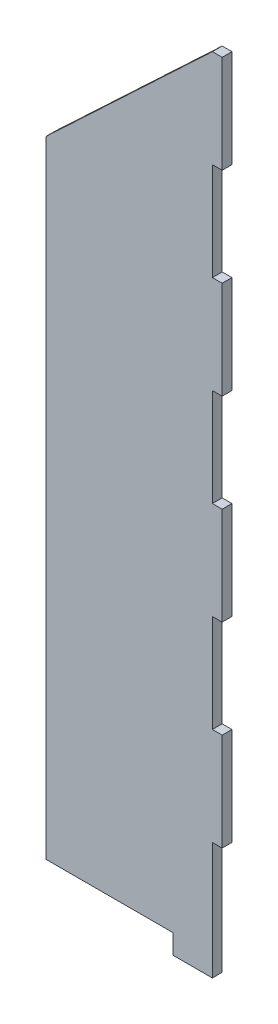
SolidWorks part; units mm, degrees
ref_plane "Front Plane" through (0, 0, 0) normal (0, 0, 1) x (1, 0, 0)
ref_plane "Top Plane" through (0, 0, 0) normal (0, 1, 0) x (1, 0, 0)
ref_plane "Right Plane" through (0, 0, 0) normal (1, 0, 0) x (0, 0, -1)
sketch "Sketch1" plane through (0, 0, 0) normal (0, 0, 1) x (1, 0, 0)
  line L0 (-26.9875, -101.6) -> (-26.9875, 101.6)
  line L1 (-26.9875, 101.6) -> (26.9875, 152.4)
  line L2 (26.9875, 152.4) -> (26.9875, -101.6)
  line L3 (26.9875, -101.6) -> (-26.9875, -101.6)
  line L4 (-26.9875, 0) -> (26.9875, 0) construction
  line L5 (26.9875, 120.65) -> (26.9875, 88.9)
  line L6 (26.9875, 152.4) -> (30.1625, 152.4)
  line L7 (26.9875, 152.4) -> (26.9875, 120.65)
  line L8 (26.9875, 120.65) -> (30.1625, 120.65)
  line L9 (30.1625, 152.4) -> (30.1625, 120.65)
  line L10 (26.9875, 120.65) -> (30.1625, 120.65)
  line L11 (30.1625, 120.65) -> (30.1625, 88.9)
  line L12 (26.9875, 88.9) -> (30.1625, 88.9)
  line L13 (26.9875, 88.9) -> (26.9875, 57.15)
  line L14 (26.9875, 88.9) -> (30.1625, 88.9)
  line L15 (30.1625, 88.9) -> (30.1625, 57.15)
  line L16 (26.9875, 57.15) -> (30.1625, 57.15)
  line L17 (26.9875, 57.15) -> (26.9875, 25.4)
  line L18 (26.9875, 57.15) -> (30.1625, 57.15)
  line L19 (30.1625, 57.15) -> (30.1625, 25.4)
  line L20 (26.9875, 25.4) -> (30.1625, 25.4)
  line L21 (26.9875, 25.4) -> (26.9875, -6.35)
  line L22 (26.9875, 25.4) -> (30.1625, 25.4)
  line L23 (30.1625, 25.4) -> (30.1625, -6.35)
  line L24 (26.9875, -6.35) -> (30.1625, -6.35)
  line L25 (26.9875, -6.35) -> (26.9875, -38.1)
  line L26 (26.9875, -6.35) -> (30.1625, -6.35)
  line L27 (30.1625, -6.35) -> (30.1625, -38.1)
  line L28 (26.9875, -38.1) -> (30.1625, -38.1)
  line L29 (26.9875, -38.1) -> (26.9875, -69.85)
  line L30 (26.9875, -38.1) -> (30.1625, -38.1)
  line L31 (30.1625, -38.1) -> (30.1625, -69.85)
  line L32 (26.9875, -69.85) -> (30.1625, -69.85)
  line L33 (26.9875, -69.85) -> (26.9875, -101.6)
  line L42 (26.9875, -69.85) -> (30.1625, -69.85)
  line L43 (30.1625, -69.85) -> (30.1625, -101.6)
  line L44 (26.9875, -101.6) -> (30.1625, -101.6)
  line L46 (14.2875, -101.6) -> (26.9875, -101.6)
  line L47 (14.2875, -101.6) -> (14.2875, -107.95)
  line L48 (14.2875, -107.95) -> (26.9875, -107.95)
  line L49 (26.9875, -101.6) -> (26.9875, -107.95)
  point P2 (0, 0)
  dimension "D1" = 53.975
  dimension "D2" = 254
  dimension "D3" = 203.2
  dimension "D4" = 3.175
  dimension "D6" = 31.75
  dimension "D7" = 12.7
  dimension "D8" = 6.35
  dimension "D5" = 8
extrude "Boss-Extrude1" add sketch "Sketch1" along normal blind 3.175
equation "\"Height\"= 12in"
equation "\"Depth\"= 7in"
equation "\"WallThickness\"= 0.125in"
equation "\"FloorThickness\"= 0.25in"
equation "\"D1@Sketch1\"=(\"Depth\"-2.75)/2"
equation "\"D4@Sketch1\"=\"WallThickness\""
equation "\"D6@Sketch1\"=\"D2@Sketch1\"/\"D5@Sketch1\""
equation "\"D8@Sketch1\"=\"FloorThickness\""
equation "\"D1@Boss-Extrude1\"=\"WallThickness\""
equation "\"Width\" = 30in"
